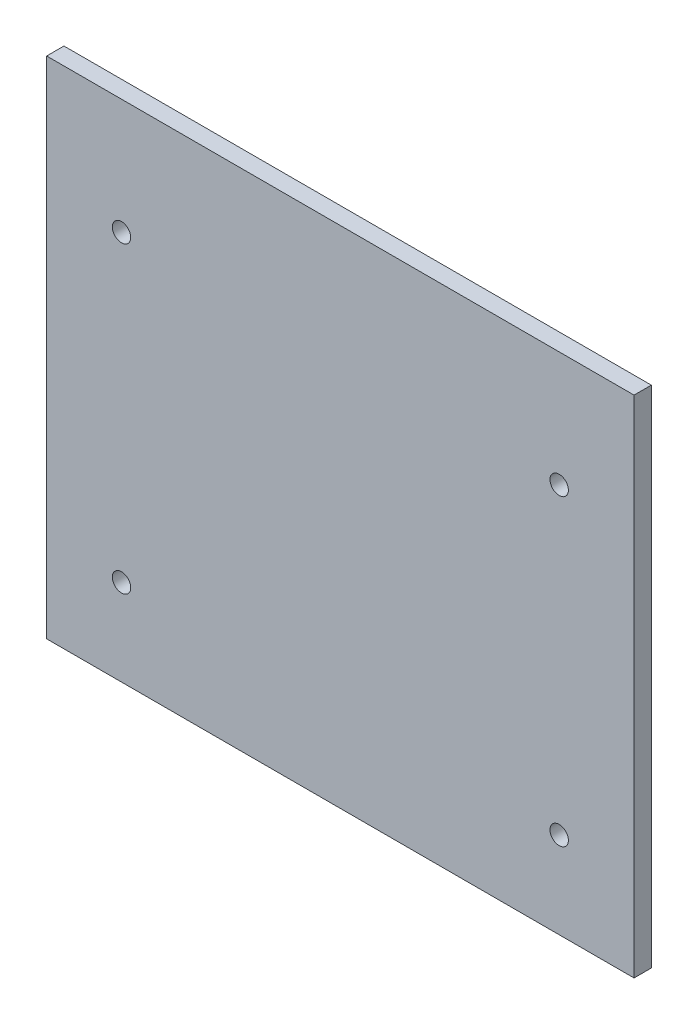
SolidWorks part; units mm, degrees
ref_plane "前视基准面" through (0, 0, 0) normal (0, 0, 1) x (1, 0, 0)
ref_plane "上视基准面" through (0, 0, 0) normal (0, 1, 0) x (1, 0, 0)
ref_plane "右视基准面" through (0, 0, 0) normal (1, 0, 0) x (0, 0, -1)
sketch "草图1" plane through (0, 0, 0) normal (0, 0, 1) x (1, 0, 0)
  line L0 (51, 1.4393) -> (51, -96.2227) construction
  line L1 (-51, -96.2227) -> (51, -96.2227)
  line L2 (-51, -96.2227) -> (-51, -8.5607)
  line L3 (-51, -8.5607) -> (51, -8.5607)
  line L4 (51, -96.2227) -> (51, -8.5607)
  line L5 (-48, 1.4393) -> (-51, 1.4393) construction
  circle A0 centre (-38, -81.2227) radius 1.6
  circle A1 centre (38, -81.2227) radius 1.6
  circle A2 centre (38, -28.5607) radius 1.6
  circle A3 centre (-38, -28.5607) radius 1.6
  dimension "D1" = 10
extrude "凸台-拉伸1" add sketch "草图1" along normal blind 3
